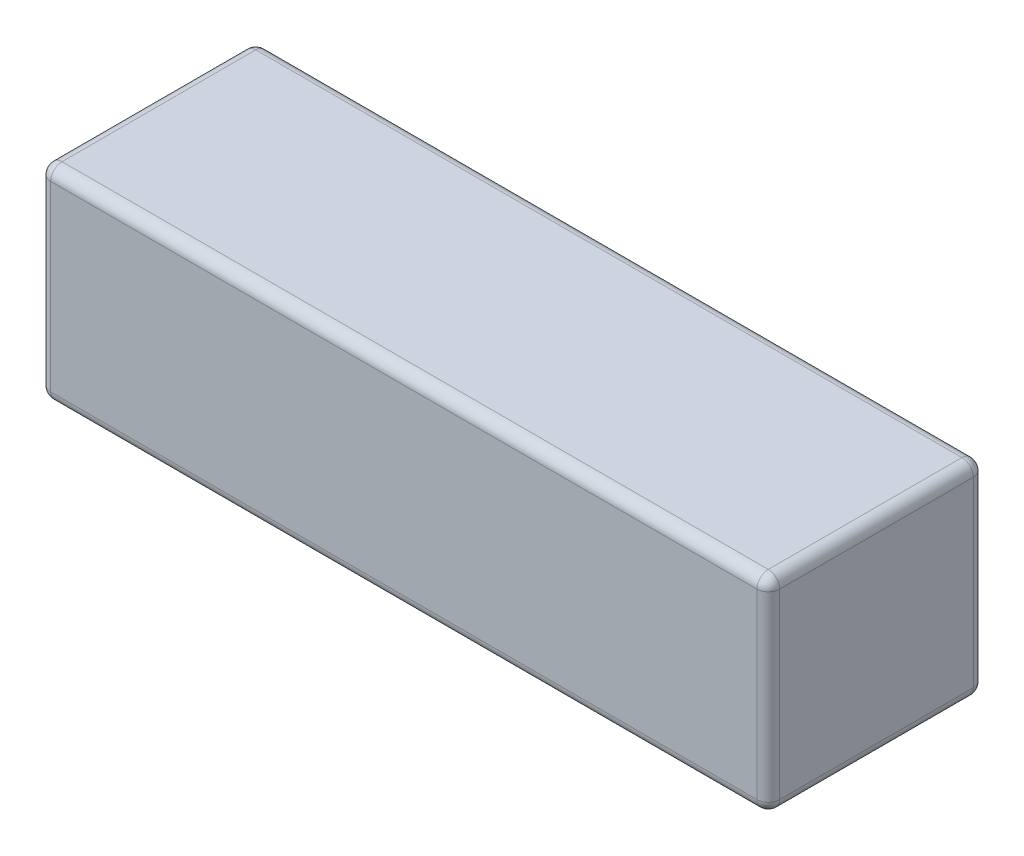
SolidWorks part; units mm, degrees
material "Default"
ref_plane "Front Plane" through (0, 0, 0) normal (0, 0, 1) x (1, 0, 0)
ref_plane "Top Plane" through (0, 0, 0) normal (0, 1, 0) x (1, 0, 0)
ref_plane "Right Plane" through (0, 0, 0) normal (1, 0, 0) x (0, 0, -1)
sketch "Sketch1" plane through (0, 0, 0) normal (0, 1, 0) x (1, 0, 0)
  line L1 (0, 0) -> (64, 0)
  line L2 (0, 0) -> (0, 19)
  line L3 (0, 19) -> (64, 19)
  line L4 (64, 0) -> (64, 19)
  dimension "D1" = 64
  dimension "D2" = 19
extrude "Boss-Extrude1" add sketch "Sketch1" along normal blind 18
fillet "Fillet1" radius 1 12 edges at (0, 9, -19) (32, 0, -19) (0, 0, -9.5) (0, 9, 0) (32, 0, 0) (64, 9, 0) (64, 9, -19) (64, 0, -9.5) (32, 18, -19) (64, 18, -9.5) (32, 18, 0) (0, 18, -9.5)
